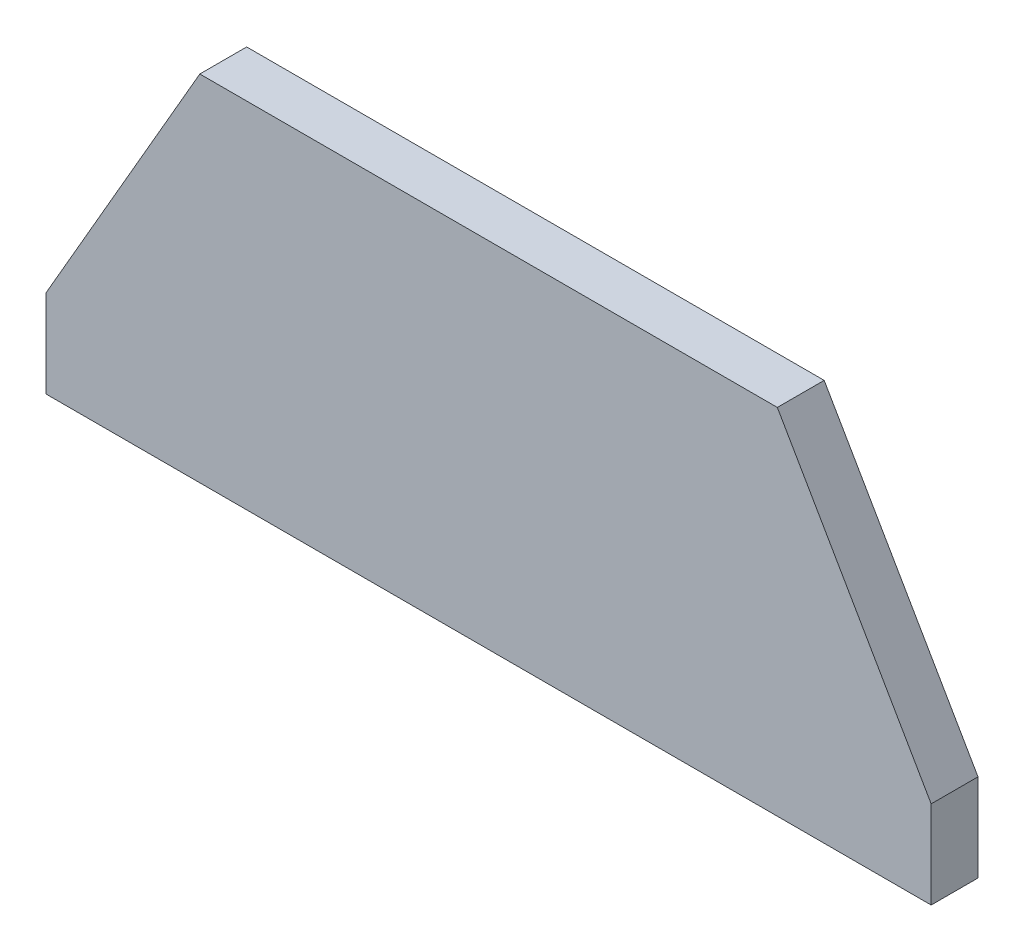
SolidWorks part; units mm, degrees
material "PLA"
ref_plane "Front Plane" through (0, 0, 0) normal (0, 0, 1) x (1, 0, 0)
ref_plane "Top Plane" through (0, 0, 0) normal (0, 1, 0) x (1, 0, 0)
ref_plane "Right Plane" through (0, 0, 0) normal (1, 0, 0) x (0, 0, -1)
sketch "Sketch1" plane through (0, 0, 0) normal (0, 0, 1) x (1, 0, 0)
  line L0 (-9.7865, 6) -> (-15, -3.03)
  line L1 (-15, 6) -> (15, 6) construction
  line L2 (-15, 6) -> (-15, -6) construction
  line L3 (-15, -6) -> (15, -6)
  line L4 (15, 6) -> (15, -6) construction
  line L5 (9.7865, 6) -> (15, -3.03)
  line L6 (-15, -6) -> (-15, -3.03)
  line L7 (-9.7865, 6) -> (9.7865, 6)
  line L8 (15, -3.03) -> (15, -6)
  point P4 (0, 6)
  point P5 (-15, 0)
  dimension "D1" = 12
  dimension "D2" = 30
  dimension "D3" = 30
  dimension "D4" = 2.97
  dimension "D5" = 2.97
  dimension "D6" = 30
extrude "Boss-Extrude1" add sketch "Sketch1" along normal mid plane 1.5875
